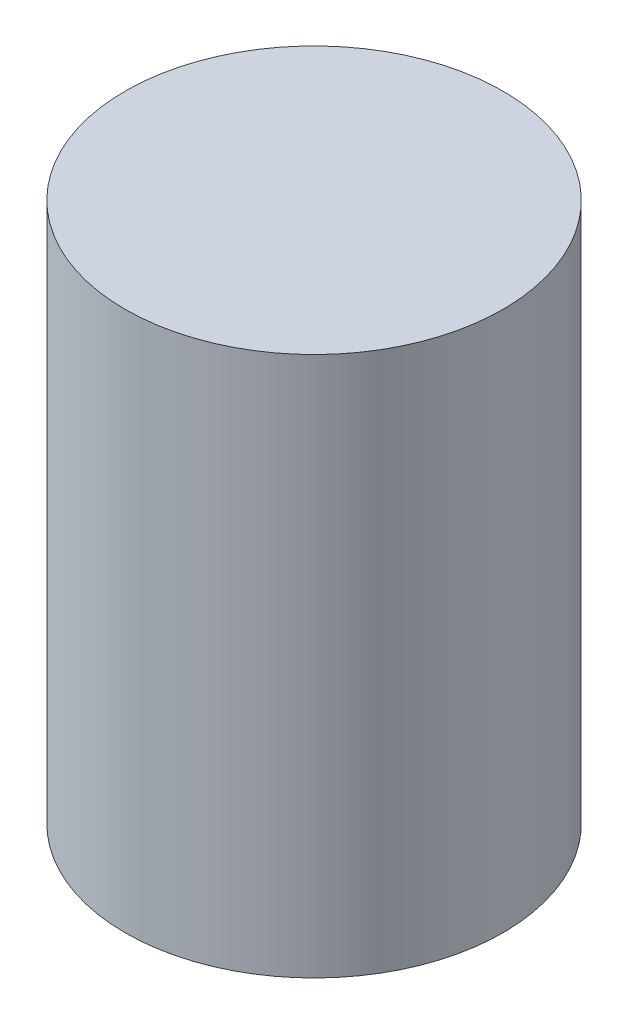
SolidWorks part; units mm, degrees
ref_plane "Plan de face" through (0, 0, 0) normal (0, 0, 1) x (1, 0, 0)
ref_plane "Plan de dessus" through (0, 0, 0) normal (0, 1, 0) x (1, 0, 0)
ref_plane "Plan de droite" through (0, 0, 0) normal (1, 0, 0) x (0, 0, -1)
sketch "Esquisse1" plane through (0, 0, 0) normal (0, 1, 0) x (1, 0, 0)
  circle A0 centre (0, 0) radius 17.5
  dimension "D1" = 35
extrude "Boss.-Extru.1" add sketch "Esquisse1" along normal blind 50
